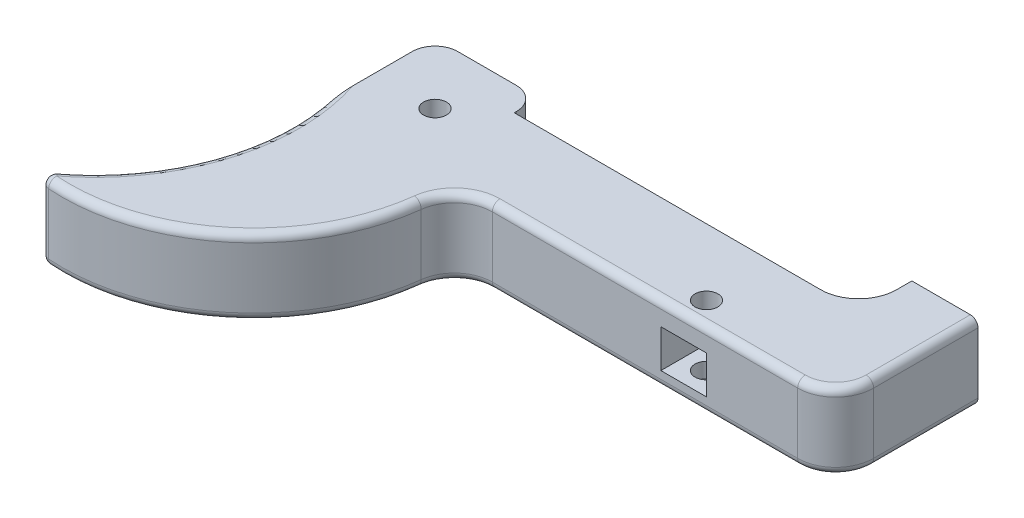
SolidWorks part; units mm, degrees
ref_plane "Alzado" through (0, 0, 0) normal (0, 0, 1) x (1, 0, 0)
ref_plane "Planta" through (0, 0, 0) normal (0, 1, 0) x (1, 0, 0)
ref_plane "Vista lateral" through (0, 0, 0) normal (1, 0, 0) x (0, 0, -1)
sketch "Croquis1" plane through (0, 0, 0) normal (0, 1, 0) x (1, 0, 0)
  line L0 (13.6999, 11.7351) -> (59.0246, 11.7351)
  line L1 (59.0246, 11.7351) -> (59.0246, 18.7351)
  line L2 (59.0246, 18.7351) -> (67.7311, 18.7351)
  line L5 (67.7311, 0) -> (17.7311, 0)
  line L8 (0, 15) -> (13.6999, 15)
  line L9 (13.6999, 15) -> (13.6999, 11.7351)
  line L10 (0, 0) -> (0, 15)
  line L11 (67.7311, 0) -> (67.7311, 18.7351)
  circle A2 centre (8, 7) radius 1.5
  arc A3 (0, 0) -> (-11.9221, -26.243) centre (-25.5911, -4.2037) cw
  arc A4 (-11.9221, -26.243) -> (17.7311, 0) centre (-7.4564, -1.4143) ccw
  dimension "D1" = 3
  dimension "D5" = 25.2272
  dimension "D6" = 7.4564
  dimension "D2" = 25.934
  dimension "D3" = 15
  dimension "D4" = 15
  dimension "D7" = 8
  dimension "D8" = 8
  dimension "D9" = 1.4143
  dimension "D10" = 25.5911
  dimension "D11" = 3.2649
  dimension "D12" = 8.7065
  dimension "D13" = 7
  dimension "D14" = 50
  dimension "D15" = 13.6999
extrude "Saliente-Extruir1" add sketch "Croquis1" along normal blind 10
fillet "Redondeo1" radius 3 2 edges at (0, 5, -15) (13.6999, 5, -15)
sketch "Croquis3" plane through (0, 10, 0) normal (0, 1, 0) x (1, 0, 0)
  line L0 (67.7311, 0) -> (67.7311, 18.7351) construction
  line L1 (17.7311, 0) -> (67.7311, 0) construction
  circle A0 centre (47.7311, 3) radius 1.5
  dimension "D1" = 3
  dimension "D2" = 20
  dimension "D3" = 3
extrude "Cortar-Extruir2" cut sketch "Croquis3" against normal blind 11
fillet "Redondeo2" radius 5 3 edges at (59.0246, 5, -11.7351) (67.7311, 5, 0) (17.7311, 5, 0)
sketch "Croquis4" plane through (0, 0, 0) normal (0, 0, 1) x (1, 0, 0)
  line L0 (67.7311, 10) -> (67.7311, 0) construction
  line L1 (44.7311, 7) -> (50.7311, 7)
  line L2 (44.7311, 7) -> (44.7311, 2)
  line L3 (44.7311, 2) -> (50.7311, 2)
  line L4 (50.7311, 7) -> (50.7311, 2)
  line L5 (22.5574, 10) -> (62.7311, 10) construction
  dimension "D1" = 6
  dimension "D2" = 5
  dimension "D3" = 17
  dimension "D4" = 3
extrude "Cortar-Extruir3" cut sketch "Croquis4" against normal blind 6
fillet "Redondeo3" radius 1 14 edges at (0, 5, 0) (-1.9794, 10, 14.9304) (-11.9221, 5, 26.243) (-1.9794, 0, 14.9304) (7.5477, 0, 21.6945) (7.5477, 10, 21.6945) (67.7311, 0, -11.8675) (66.2667, 0, -1.4645) (42.6443, 0, 0) (19.2382, 0, 1.2606) (67.7311, 10, -11.8675) (66.2667, 10, -1.4645) (42.6443, 10, 0) (19.2382, 10, 1.2606)
